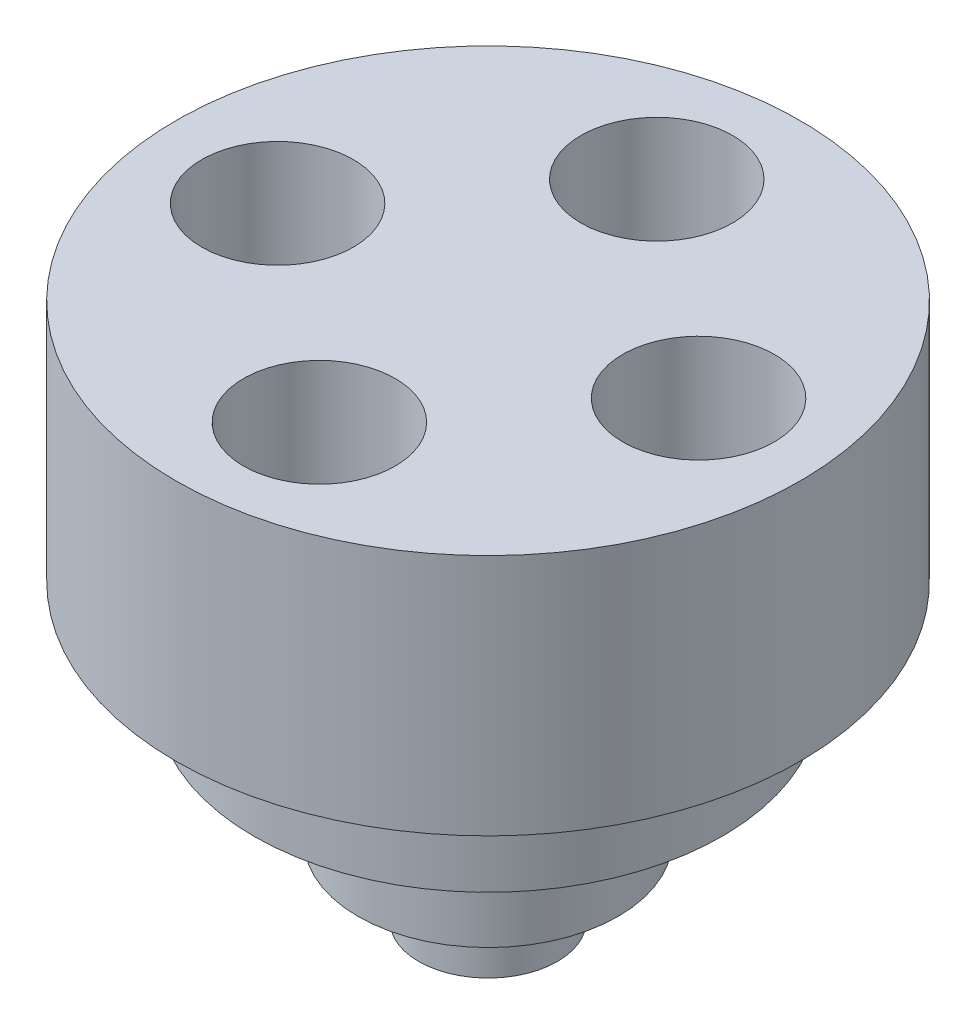
SolidWorks part; units mm, degrees
ref_plane "前视基准面" through (0, 0, 0) normal (0, 0, 1) x (1, 0, 0)
ref_plane "上视基准面" through (0, 0, 0) normal (0, 1, 0) x (1, 0, 0)
ref_plane "右视基准面" through (0, 0, 0) normal (1, 0, 0) x (0, 0, -1)
sketch "草图1" plane through (0, 0, 0) normal (0, 1, 0) x (1, 0, 0)
  circle A0 centre (0, 0) radius 9.525
  dimension "D1" = 19.05
extrude "凸台-拉伸1" add sketch "草图1" along normal blind 16.51
sketch "草图2" plane through (0, 16.51, 0) normal (0, 1, 0) x (1, 0, 0)
  circle A0 centre (0, 0) radius 22.86
  dimension "D1" = 45.72
extrude "凸台-拉伸2" add sketch "草图2" along normal blind 17.78
sketch "草图3" plane through (0, 34.29, 0) normal (0, 1, 0) x (1, 0, 0)
  circle A0 centre (-13.8859, -1.5306) radius 5.5563
  circle A1 centre (-1.5306, 13.8859) radius 5.5563
  circle A2 centre (13.8859, 1.5306) radius 5.5563
  circle A3 centre (1.5306, -13.8859) radius 5.5563
  circle A4 centre (0, 0) radius 22.86 construction
  point P13 (0, 0)
  dimension "D1" = 11.1125
  dimension "D4" = 13.97
  dimension "D2" = 4
sketch "草图4" plane through (0, 0, 0) normal (0, -1, 0) x (1, 0, 0)
  line L0 (3.0805, 0.7689) -> (0.8744, 3.0522)
  arc A0 (0.8744, 3.0522) -> (3.0805, 0.7689) centre (0, 0) ccw
  dimension "D1" = 6.35
  dimension "D2" = 3.175
extrude "切除-拉伸1" cut sketch "草图4" against normal blind 10.16
extrude "切除-拉伸2" cut sketch "草图3" against normal blind 11.1125
ref_plane "基准面1" through (-7.156, 0, -6.9139) normal (-0.7192, 0, -0.6948) x (-0.6948, 0, 0.7192)
ref_axis "基准轴1" through (0, 16.51, 0) along (0, -1, 0)
ref_plane "基准面2" through (0, 0, 0) normal (-0.0172, 0, -0.9999) x (0, -1, 0)
sketch "草图5" plane through (-7.156, 0, -6.9139) normal (-0.7192, 0, -0.6948) x (-0.6948, 0, 0.7192)
  line L0 (-9.525, 0) -> (9.525, 0) construction
  circle A0 centre (0, 5.08) radius 1.55
  dimension "D1" = 3.1
  dimension "D2" = 5.08
extrude "切除-拉伸3" cut sketch "草图5" against normal blind 32 contours A0
sketch "草图6" plane through (0, 0, 0) normal (-0.0172, 0, -0.9999) x (-0.9999, 0, 0.0172)
  line L0 (-9.525, 16.51) -> (-9.525, 8.89)
  line L1 (-9.525, 16.51) -> (-9.525, 0) construction
  line L2 (-22.86, 16.51) -> (22.86, 16.51) construction
  line L3 (-9.525, 8.89) -> (-17.145, 8.89)
  line L4 (-17.145, 8.89) -> (-17.145, 16.51)
  line L5 (-17.145, 16.51) -> (-9.525, 16.51)
  dimension "D1" = 7.62
  dimension "D2" = 7.62
revolve "旋转2" add sketch "草图6" angle 360 about axis through (0, 16.51, 0) along (0, -1, 0)
sketch "草图7" plane through (0, 0, 0) normal (0, -1, 0) x (1, 0, 0)
  line L0 (0.8744, 3.0522) -> (3.0805, 0.7689)
  arc A0 (0.8744, 3.0522) -> (3.0805, 0.7689) centre (0, 0) ccw
  circle A1 centre (0, 0) radius 5.08
  dimension "D1" = 10.16
extrude "凸台-拉伸3" add sketch "草图7" along normal blind 5.08
